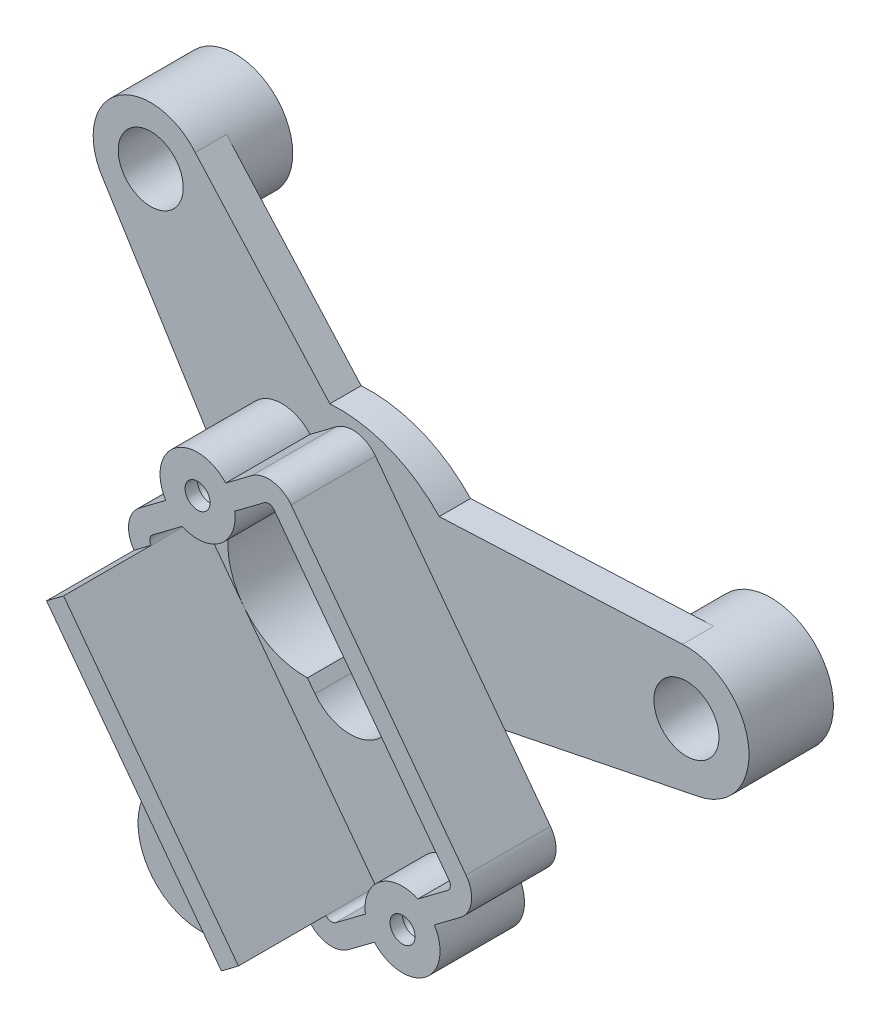
SolidWorks part; units mm, degrees
ref_plane "Front Plane" through (0, 0, 0) normal (0, 0, 1) x (1, 0, 0)
ref_plane "Top Plane" through (0, 0, 0) normal (0, 1, 0) x (1, 0, 0)
ref_plane "Right Plane" through (0, 0, 0) normal (1, 0, 0) x (0, 0, -1)
sketch "Sketch1" plane through (0, 0, 0) normal (0, 0, 1) x (1, 0, 0)
  circle A0 centre (19.3675, 34.629) radius 5
  circle A1 centre (-19.4667, 5.5033) radius 5
  circle A2 centre (-23.4496, 51.2661) radius 4.6
extrude "Boss-Extrude1" add sketch "Sketch1" along normal offset from surface (4.25 mm away) 0.25
sketch "Sketch2" plane through (0, 0, 4.25) normal (0, 0, 1) x (1, 0, 0)
  line L0 (-9.3192, 38.6435) -> (18.3285, 39.5198)
  line L1 (-9.3192, 38.6435) -> (-7.4808, 23.7565) construction
  line L2 (-8.4, 31.2) -> (19.3675, 34.629) construction
  line L3 (-7.4808, 23.7565) -> (19.5495, 29.6323)
  line L4 (-23.4496, 51.2661) -> (-8.4, 31.2) construction
  line L5 (-19.4667, 5.5033) -> (-8.4, 31.2) construction
  line L6 (-20.1134, 54.4331) -> (-2.9605, 36.3635)
  line L7 (-27.424, 48.9501) -> (-13.8395, 26.0365)
  line L8 (-2.9605, 36.3635) -> (-13.8395, 26.0365)
  line L9 (-27.424, 48.9501) -> (-20.1134, 54.4331) construction
  line L10 (19.5495, 29.6323) -> (18.3285, 39.5198) construction
  circle A0 centre (-8.4, 31.2) radius 7.5
  circle A1 centre (-8.4, 31.2) radius 19.5 construction
  circle A2 centre (19.3675, 34.629) radius 5 construction
  circle A3 centre (-19.4667, 5.5033) radius 5 construction
  circle A4 centre (-23.4496, 51.2661) radius 4.6 construction
  circle A5 centre (-19.4667, 5.5033) radius 5
  circle A6 centre (-23.4496, 51.2661) radius 4.6
  circle A7 centre (19.3675, 34.629) radius 5
  point P25 (18.939, 34.5761)
  point P27 (-23.7687, 51.6916)
  dimension "D1" = 15
sketch "Sketch3" plane through (0, 0, 4.25) normal (0, 0, 1) x (1, 0, 0)
  line L0 (-2.2049, 28.2739) -> (-2.9073, 29.2103) construction
  line L1 (-8.0279, 25.3699) -> (-7.3256, 24.4334) construction
  line L2 (-2.2049, 28.2739) -> (-2.9073, 29.2103) construction
  line L3 (-8.0279, 25.3699) -> (-7.3256, 24.4334) construction
  line L4 (-8.1722, 25.0622) -> (-7.5656, 24.2534)
  line L5 (-1.9649, 28.4539) -> (-2.5715, 29.2627)
  line L6 (-19.8956, 54.1866) -> (-9.1317, 42.1756)
  line L7 (-27.2483, 48.672) -> (-18.7317, 34.9756)
  line L8 (-23.4496, 51.2661) -> (-8.4, 31.2) construction
  line L9 (-8.4, 31.2) -> (19.3675, 34.629) construction
  line L10 (19.3675, 34.629) -> (-19.4667, 5.5033) construction
  line L11 (-19.4667, 5.5033) -> (-8.4, 31.2) construction
  line L12 (-18.7317, 34.9756) -> (-9.1317, 42.1756) construction
  line L13 (19.0518, 39.619) -> (-0.3894, 38.7386)
  line L14 (20.2752, 29.7121) -> (1.2038, 25.8366)
  line L15 (-27.2483, 48.672) -> (-19.8956, 54.1866) construction
  line L16 (1.2038, 25.8366) -> (-0.3894, 38.7386) construction
  line L17 (20.2752, 29.7121) -> (19.0518, 39.619) construction
  line L18 (-24.1175, 7.3393) -> (-14.816, 3.6673) construction
  line L19 (-17.5668, 25.1197) -> (-24.1175, 7.3393)
  line L20 (-14.816, 3.6673) -> (-5.9402, 20.4786)
  line L21 (-5.9402, 20.4786) -> (-17.88, 25.6206) construction
  arc A0 (-2.9073, 29.2103) -> (-3.7264, 34.7052) centre (-8.4, 31.2) ccw construction
  arc A1 (-2.845, 23.7934) -> (-2.2049, 28.2739) centre (-4.7653, 26.3537) ccw construction
  arc A2 (-7.3256, 24.4334) -> (-2.845, 23.7934) centre (-4.7653, 26.3537) ccw construction
  arc A3 (-13.0736, 27.6948) -> (-8.0279, 25.3699) centre (-8.4, 31.2) ccw construction
  arc A4 (-3.7264, 34.7052) -> (-13.0736, 27.6948) centre (-8.4, 31.2) ccw construction
  arc A5 (-2.9073, 29.2103) -> (-3.7264, 34.7052) centre (-8.4, 31.2) ccw construction
  arc A6 (-2.845, 23.7934) -> (-2.2049, 28.2739) centre (-4.7653, 26.3537) ccw construction
  arc A7 (-7.3256, 24.4334) -> (-2.845, 23.7934) centre (-4.7653, 26.3537) ccw construction
  arc A8 (-13.0736, 27.6948) -> (-8.0279, 25.3699) centre (-8.4, 31.2) ccw construction
  arc A9 (-3.7264, 34.7052) -> (-13.0736, 27.6948) centre (-8.4, 31.2) ccw construction
  arc A10 (-2.5715, 29.2627) -> (-3.4864, 34.8852) centre (-8.4, 31.2) ccw
  arc A11 (-3.4864, 34.8852) -> (-13.3136, 27.5148) centre (-8.4, 31.2) ccw
  arc A12 (-13.3136, 27.5148) -> (-8.1722, 25.0622) centre (-8.4, 31.2) ccw
  arc A13 (-7.5656, 24.2534) -> (-2.665, 23.5534) centre (-4.7653, 26.3537) ccw
  arc A14 (-2.665, 23.5534) -> (-1.9649, 28.4539) centre (-4.7653, 26.3537) ccw
  circle A15 centre (19.3675, 34.629) radius 5 construction
  circle A16 centre (-19.4667, 5.5033) radius 5 construction
  circle A17 centre (-23.4496, 51.2661) radius 4.6 construction
  arc A18 (20.2752, 29.7121) -> (19.0518, 39.619) centre (19.3675, 34.629) ccw
  arc A19 (-24.1175, 7.3393) -> (-14.816, 3.6673) centre (-19.4667, 5.5033) ccw
  arc A20 (-19.8956, 54.1866) -> (-27.2483, 48.672) centre (-23.4496, 51.2661) ccw
  arc A21 (2.6287, 14.8335) -> (4.2238, 16.0299) centre (3.4262, 15.4317) ccw construction
  arc A22 (4.2238, 16.0299) -> (2.6287, 14.8335) centre (3.4262, 15.4317) ccw construction
  arc A23 (-12.1592, 37.8739) -> (-13.7543, 36.6775) centre (-12.9568, 37.2757) ccw construction
  arc A24 (-13.7543, 36.6775) -> (-12.1592, 37.8739) centre (-12.9568, 37.2757) ccw construction
  arc A25 (2.6287, 14.8335) -> (4.2238, 16.0299) centre (3.4262, 15.4317) ccw construction
  arc A26 (4.2238, 16.0299) -> (2.6287, 14.8335) centre (3.4262, 15.4317) ccw construction
  arc A27 (-12.1592, 37.8739) -> (-13.7543, 36.6775) centre (-12.9568, 37.2757) ccw construction
  arc A28 (-13.7543, 36.6775) -> (-12.1592, 37.8739) centre (-12.9568, 37.2757) ccw construction
  arc A29 (-0.3894, 38.7386) -> (-9.1317, 42.1756) centre (-8.4, 31.2) ccw
  arc A30 (2.5171, 32.5481) -> (-0.3894, 38.7386) centre (-8.4, 31.2) ccw construction
  arc A31 (1.2038, 25.8366) -> (2.5171, 32.5481) centre (-8.4, 31.2) ccw construction
  arc A32 (-5.9402, 20.4786) -> (1.2038, 25.8366) centre (-8.4, 31.2) ccw
  arc A33 (-12.751, 21.0971) -> (-5.9402, 20.4786) centre (-8.4, 31.2) ccw construction
  arc A34 (-17.5668, 25.1197) -> (-12.751, 21.0971) centre (-8.4, 31.2) ccw construction
  arc A35 (-18.7317, 34.9756) -> (-17.5668, 25.1197) centre (-8.4, 31.2) ccw
  arc A36 (-15, 40) -> (-18.7317, 34.9756) centre (-8.4, 31.2) ccw construction
  arc A37 (-9.1317, 42.1756) -> (-15, 40) centre (-8.4, 31.2) ccw construction
  arc A38 (15.3675, 31.629) -> (20.2752, 29.7121) centre (19.3675, 34.629) ccw construction
  arc A39 (14.4052, 34.0162) -> (15.3675, 31.629) centre (19.3675, 34.629) ccw construction
  arc A40 (19.0518, 39.619) -> (14.4052, 34.0162) centre (19.3675, 34.629) ccw construction
  arc A41 (-20.6896, 47.5861) -> (-19.8956, 54.1866) centre (-23.4496, 51.2661) ccw construction
  arc A42 (-27.2483, 48.672) -> (-20.6896, 47.5861) centre (-23.4496, 51.2661) ccw construction
  arc A43 (-17.489, 10.0955) -> (-24.1175, 7.3393) centre (-19.4667, 5.5033) ccw construction
  arc A44 (-15.4667, 8.5033) -> (-17.489, 10.0955) centre (-19.4667, 5.5033) ccw construction
  arc A45 (-14.816, 3.6673) -> (-15.4667, 8.5033) centre (-19.4667, 5.5033) ccw construction
  point P36 (-9.1317, 42.1756)
  point P44 (-13.9317, 38.5756)
  point P49 (-23.572, 51.4293)
  point P50 (0.4072, 32.2876)
  point P51 (19.6635, 34.6655)
  point P52 (-19.4667, 5.5033)
  point P57 (-11.9101, 23.0496)
  dimension "D2" = 22
  dimension "D3" = 12
  dimension "D4" = 13
  dimension "D1" = 0.3
extrude "Boss-Extrude2" add sketch "Sketch3" along normal blind 2.5
sketch "Sketch4" plane through (0, 0, 6.75) normal (0, 0, 1) x (1, 0, 0)
  line L0 (-2.0957, 13.481) -> (6.8451, 20.1866) construction
  line L1 (6.6673, 20.847) -> (-3.7264, 34.7052) construction
  line L2 (-3.7264, 34.7052) -> (-7.003, 39.074) construction
  line L3 (-13.0736, 27.6948) -> (-2.6799, 13.8366) construction
  line L4 (-16.3502, 32.0636) -> (-13.0736, 27.6948) construction
  line L5 (-7.4348, 39.2264) -> (-11.9052, 35.8736) construction
  line L6 (-11.9052, 35.8736) -> (-16.3756, 32.5208) construction
  line L7 (-2.0957, 13.481) -> (6.8451, 20.1866)
  line L8 (6.6673, 20.847) -> (-3.7264, 34.7052)
  line L9 (-3.7264, 34.7052) -> (-7.003, 39.074)
  line L10 (-13.0736, 27.6948) -> (-2.6799, 13.8366)
  line L11 (-16.3502, 32.0636) -> (-13.0736, 27.6948)
  line L12 (-7.4348, 39.2264) -> (-11.9052, 35.8736)
  line L13 (-11.9052, 35.8736) -> (-16.3756, 32.5208)
  line L14 (6.6673, 20.847) -> (6.8959, 20.5422)
  line L15 (-2.6799, 13.8366) -> (-2.4513, 13.5318)
  line L16 (-16.4264, 32.1652) -> (-16.3502, 32.0636)
  line L17 (-7.0792, 39.1756) -> (-7.003, 39.074)
  arc A0 (-2.4513, 13.5318) -> (-2.0957, 13.481) centre (-2.2481, 13.6842) ccw construction
  arc A1 (6.8451, 20.1866) -> (6.8959, 20.5422) centre (6.6927, 20.3898) ccw construction
  arc A2 (-7.0792, 39.1756) -> (-7.4348, 39.2264) centre (-7.2824, 39.0232) ccw construction
  arc A3 (-16.3756, 32.5208) -> (-16.4264, 32.1652) centre (-16.2232, 32.3176) ccw construction
  arc A4 (-2.4513, 13.5318) -> (-2.0957, 13.481) centre (-2.2481, 13.6842) ccw
  arc A5 (6.8451, 20.1866) -> (6.8959, 20.5422) centre (6.6927, 20.3898) ccw
  arc A6 (-7.0792, 39.1756) -> (-7.4348, 39.2264) centre (-7.2824, 39.0232) ccw
  arc A7 (-16.3756, 32.5208) -> (-16.4264, 32.1652) centre (-16.2232, 32.3176) ccw
  arc A8 (2.6287, 14.8335) -> (4.2238, 16.0299) centre (3.4262, 15.4317) ccw construction
  arc A9 (4.2238, 16.0299) -> (2.6287, 14.8335) centre (3.4262, 15.4317) ccw construction
  arc A10 (-12.1592, 37.8739) -> (-13.7543, 36.6775) centre (-12.9568, 37.2757) ccw construction
  arc A11 (-13.7543, 36.6775) -> (-12.1592, 37.8739) centre (-12.9568, 37.2757) ccw construction
  arc A12 (2.6287, 14.8335) -> (4.2238, 16.0299) centre (3.4262, 15.4317) ccw
  arc A13 (4.2238, 16.0299) -> (2.6287, 14.8335) centre (3.4262, 15.4317) ccw
  arc A14 (-12.1592, 37.8739) -> (-13.7543, 36.6775) centre (-12.9568, 37.2757) ccw
  arc A15 (-13.7543, 36.6775) -> (-12.1592, 37.8739) centre (-12.9568, 37.2757) ccw
sketch "Sketch5" plane through (0, 0, 6.75) normal (0, 0, 1) x (1, 0, 0)
  line L3 (-8.1722, 25.0622) -> (-7.5656, 24.2534)
  line L4 (-1.9649, 28.4539) -> (-2.5715, 29.2627)
  line L5 (-8.1722, 25.0622) -> (-7.5656, 24.2534)
  line L18 (-1.9649, 28.4539) -> (-2.5715, 29.2627)
  line L39 (8.2673, 22.047) -> (-2.1264, 35.9052)
  line L40 (-2.1264, 35.9052) -> (-5.403, 40.274)
  line L41 (-5.403, 40.274) -> (-5.4792, 40.3756)
  line L42 (-8.6348, 40.8264) -> (-13.1052, 37.4736)
  line L43 (-13.1052, 37.4736) -> (-17.5756, 34.1208)
  line L44 (-18.0264, 30.9652) -> (-17.9502, 30.8636)
  line L45 (-17.9502, 30.8636) -> (-14.6736, 26.4948)
  line L46 (-14.6736, 26.4948) -> (-4.2799, 12.6366)
  line L47 (-4.2799, 12.6366) -> (-4.0513, 12.3318)
  line L48 (-0.8957, 11.881) -> (8.0451, 18.5866)
  line L49 (8.4959, 21.7422) -> (8.2673, 22.047)
  line L50 (8.2673, 22.047) -> (-2.1264, 35.9052)
  line L51 (-2.1264, 35.9052) -> (-5.403, 40.274)
  line L52 (-5.403, 40.274) -> (-5.4792, 40.3756)
  line L53 (-8.6348, 40.8264) -> (-13.1052, 37.4736)
  line L54 (-13.1052, 37.4736) -> (-17.5756, 34.1208)
  line L55 (-18.0264, 30.9652) -> (-17.9502, 30.8636)
  line L56 (-17.9502, 30.8636) -> (-14.6736, 26.4948)
  line L57 (-14.6736, 26.4948) -> (-4.2799, 12.6366)
  line L58 (-4.2799, 12.6366) -> (-4.0513, 12.3318)
  line L59 (-0.8957, 11.881) -> (8.0451, 18.5866)
  line L60 (8.4959, 21.7422) -> (8.2673, 22.047)
  arc A0 (-2.5715, 29.2627) -> (-8.1722, 25.0622) centre (-8.4, 31.2) ccw construction
  arc A1 (-2.5715, 29.2627) -> (-8.1722, 25.0622) centre (-8.4, 31.2) ccw
  arc A4 (-2.5715, 29.2627) -> (-8.1722, 25.0622) centre (-8.4, 31.2) ccw
  arc A5 (-7.5656, 24.2534) -> (-1.9649, 28.4539) centre (-4.7653, 26.3537) ccw
  arc A18 (-2.5715, 29.2627) -> (-8.1722, 25.0622) centre (-8.4, 31.2) ccw
  arc A19 (-7.5656, 24.2534) -> (-1.9649, 28.4539) centre (-4.7653, 26.3537) ccw
  arc A26 (-5.4792, 40.3756) -> (-8.6348, 40.8264) centre (-7.2824, 39.0232) ccw
  arc A27 (-17.5756, 34.1208) -> (-18.0264, 30.9652) centre (-16.2232, 32.3176) ccw
  arc A28 (-4.0513, 12.3318) -> (-0.8957, 11.881) centre (-2.2481, 13.6842) ccw
  arc A29 (8.0451, 18.5866) -> (8.4959, 21.7422) centre (6.6927, 20.3898) ccw
  arc A30 (-5.4792, 40.3756) -> (-8.6348, 40.8264) centre (-7.2824, 39.0232) ccw
  arc A31 (-17.5756, 34.1208) -> (-18.0264, 30.9652) centre (-16.2232, 32.3176) ccw
  arc A32 (-4.0513, 12.3318) -> (-0.8957, 11.881) centre (-2.2481, 13.6842) ccw
  arc A33 (8.0451, 18.5866) -> (8.4959, 21.7422) centre (6.6927, 20.3898) ccw
  point P1 (-8.4, 31.2)
  point P2 (0.7498, 28.1587)
  point P3 (-8.0423, 21.5646)
  point P6 (-10.3656, 22.1534)
  point P7 (-4.7653, 26.3537)
  point P8 (0.8351, 30.5539)
  dimension "D1" = 2
  dimension "D2" = 0
extrude "Boss-Extrude3" add sketch "Sketch5" along normal blind 2.75
sketch "Sketch6" plane through (0, 0, 9.5) normal (0, 0, 1) x (1, 0, 0)
  line L11 (-8.6348, 40.8264) -> (-13.1052, 37.4736) construction
  line L12 (-13.1052, 37.4736) -> (-17.5756, 34.1208) construction
  line L13 (-18.0264, 30.9652) -> (-17.9502, 30.8636) construction
  line L14 (-17.9502, 30.8636) -> (-14.6736, 26.4948) construction
  line L15 (-14.6736, 26.4948) -> (-4.2799, 12.6366) construction
  line L16 (-4.2799, 12.6366) -> (-4.0513, 12.3318) construction
  line L17 (-0.8957, 11.881) -> (8.0451, 18.5866) construction
  line L18 (8.4959, 21.7422) -> (8.2673, 22.047) construction
  line L19 (8.2673, 22.047) -> (-2.1264, 35.9052) construction
  line L20 (-2.1264, 35.9052) -> (-5.403, 40.274) construction
  line L21 (-5.403, 40.274) -> (-5.4792, 40.3756) construction
  line L22 (6.9073, 21.027) -> (-3.4864, 34.8852)
  line L23 (7.1359, 20.7222) -> (6.9073, 21.027)
  line L24 (-1.9157, 13.241) -> (7.0251, 19.9466)
  line L25 (-2.9199, 13.6566) -> (-2.6913, 13.3518)
  line L26 (-13.3136, 27.5148) -> (-2.9199, 13.6566)
  line L27 (-16.5902, 31.8836) -> (-13.3136, 27.5148)
  line L28 (-16.6664, 31.9852) -> (-16.5902, 31.8836)
  line L29 (-12.0852, 36.1136) -> (-16.5556, 32.7608)
  line L30 (-7.6148, 39.4664) -> (-12.0852, 36.1136)
  line L31 (-6.763, 39.254) -> (-6.8392, 39.3556)
  line L32 (-3.4864, 34.8852) -> (-6.763, 39.254)
  line L33 (6.9073, 21.027) -> (-3.4864, 34.8852)
  line L34 (7.1359, 20.7222) -> (6.9073, 21.027)
  line L35 (-1.9157, 13.241) -> (7.0251, 19.9466)
  line L36 (-2.9199, 13.6566) -> (-2.6913, 13.3518)
  line L37 (-13.3136, 27.5148) -> (-2.9199, 13.6566)
  line L38 (-16.5902, 31.8836) -> (-13.3136, 27.5148)
  line L39 (-16.6664, 31.9852) -> (-16.5902, 31.8836)
  line L40 (-12.0852, 36.1136) -> (-16.5556, 32.7608)
  line L41 (-7.6148, 39.4664) -> (-12.0852, 36.1136)
  line L42 (-6.763, 39.254) -> (-6.8392, 39.3556)
  line L43 (-3.4864, 34.8852) -> (-6.763, 39.254)
  line L44 (-8.6348, 40.8264) -> (-13.1052, 37.4736)
  line L45 (-13.1052, 37.4736) -> (-17.5756, 34.1208)
  line L46 (-18.0264, 30.9652) -> (-17.9502, 30.8636)
  line L47 (-17.9502, 30.8636) -> (-14.6736, 26.4948)
  line L48 (-14.6736, 26.4948) -> (-4.2799, 12.6366)
  line L49 (-4.2799, 12.6366) -> (-4.0513, 12.3318)
  line L50 (-0.8957, 11.881) -> (8.0451, 18.5866)
  line L51 (8.4959, 21.7422) -> (8.2673, 22.047)
  line L52 (8.2673, 22.047) -> (-2.1264, 35.9052)
  line L53 (-2.1264, 35.9052) -> (-5.403, 40.274)
  line L54 (-5.403, 40.274) -> (-5.4792, 40.3756)
  arc A4 (-5.4792, 40.3756) -> (-8.6348, 40.8264) centre (-7.2824, 39.0232) ccw construction
  arc A5 (-17.5756, 34.1208) -> (-18.0264, 30.9652) centre (-16.2232, 32.3176) ccw construction
  arc A6 (-4.0513, 12.3318) -> (-0.8957, 11.881) centre (-2.2481, 13.6842) ccw construction
  arc A7 (8.0451, 18.5866) -> (8.4959, 21.7422) centre (6.6927, 20.3898) ccw construction
  arc A8 (7.0251, 19.9466) -> (7.1359, 20.7222) centre (6.6927, 20.3898) ccw
  arc A9 (-2.6913, 13.3518) -> (-1.9157, 13.241) centre (-2.2481, 13.6842) ccw
  arc A10 (-16.5556, 32.7608) -> (-16.6664, 31.9852) centre (-16.2232, 32.3176) ccw
  arc A11 (-6.8392, 39.3556) -> (-7.6148, 39.4664) centre (-7.2824, 39.0232) ccw
  arc A12 (7.0251, 19.9466) -> (7.1359, 20.7222) centre (6.6927, 20.3898) ccw
  arc A13 (-2.6913, 13.3518) -> (-1.9157, 13.241) centre (-2.2481, 13.6842) ccw
  arc A14 (-16.5556, 32.7608) -> (-16.6664, 31.9852) centre (-16.2232, 32.3176) ccw
  arc A15 (-6.8392, 39.3556) -> (-7.6148, 39.4664) centre (-7.2824, 39.0232) ccw
  arc A16 (-5.4792, 40.3756) -> (-8.6348, 40.8264) centre (-7.2824, 39.0232) ccw
  arc A17 (-17.5756, 34.1208) -> (-18.0264, 30.9652) centre (-16.2232, 32.3176) ccw
  arc A18 (-4.0513, 12.3318) -> (-0.8957, 11.881) centre (-2.2481, 13.6842) ccw
  arc A19 (8.0451, 18.5866) -> (8.4959, 21.7422) centre (6.6927, 20.3898) ccw
  dimension "D1" = 0.3
extrude "Boss-Extrude4" add sketch "Sketch6" along normal blind 4
sketch "Sketch7" plane through (0, 0, 13.5) normal (0, 0, 1) x (1, 0, 0)
  line L0 (-8.6348, 40.8264) -> (-17.5756, 34.1208) construction
  line L1 (-10.7134, 39.2675) -> (-15.497, 35.6797) construction
  circle A0 centre (-12.9568, 37.2757) radius 3
  circle A1 centre (3.4262, 15.4317) radius 3
  dimension "D1" = 6
extrude "Boss-Extrude5" add sketch "Sketch7" against normal up to surface (6.75 mm away)
sketch "Sketch8" plane through (0, 0, 13.5) normal (0, 0, 1) x (1, 0, 0)
  line L0 (-16.6664, 31.9852) -> (-18.0264, 30.9652)
  line L1 (-18.0264, 30.9652) -> (-4.0513, 12.3318)
  line L2 (-4.0513, 12.3318) -> (-2.6913, 13.3518)
  line L3 (-2.6913, 13.3518) -> (-16.6664, 31.9852)
extrude "Boss-Extrude6" add sketch "Sketch8" along normal blind 7
hole_wizard "Ø2.0 (2) Diameter Hole1" positions "Sketch9" profile "Sketch10" hole size "Ø2.0" standard "DIN"
sketch "Sketch9" plane through (0, 0, 13.5) normal (0, 0, 1) x (1, 0, 0)
  point P0 (-12.9568, 37.2757)
  point P3 (3.4262, 15.4317)
sketch "Sketch10" plane through (-12.9568, 37.2757, 13.5) normal (1, 0, 0) x (0, -1, 0)
  line L0 (0, 0) -> (0, 4.7321)
  line L1 (0, 4.7321) -> (1, 1)
  line L2 (1, 1) -> (1, 0)
  line L5 (1, 0) -> (0, 0)
  line L10 (0, 4.7321) -> (-1, 1) construction
  line L11 (0, -6.35) -> (0, 107.95) construction
  dimension "Hole Dia." = 2
  dimension "Hole Depth" = 1
  dimension "Drill Angle" = 30
hole_wizard "Ø5.2 (5.2) Diameter Hole1" positions "Sketch11" profile "Sketch12" hole size "Ø5.2" standard "DIN"
sketch "Sketch11" plane through (-108.7264, 76.7906, -28) normal (0, 0, -1) x (-0.6, 0.8, 0)
  point P0 (-110.5857, 28.6353)
  point P3 (-71.5857, 52.9068)
  point P6 (-110.5857, 77.1782)
sketch "Sketch12" plane through (-19.4667, 5.5033, -28) normal (1, 0, 0) x (0, 1, 0)
  line L0 (0, 0) -> (0, 42.5622)
  line L1 (0, 42.5622) -> (2.6, 41)
  line L2 (2.6, 41) -> (2.6, 0)
  line L3 (2.6, 0) -> (0, 0)
  line L4 (0, 42.5622) -> (-2.6, 41) construction
  line L5 (0, -6.35) -> (0, 107.95) construction
  dimension "Hole Dia." = 5.2
  dimension "Hole Depth" = 41
  dimension "Drill Angle" = 118
